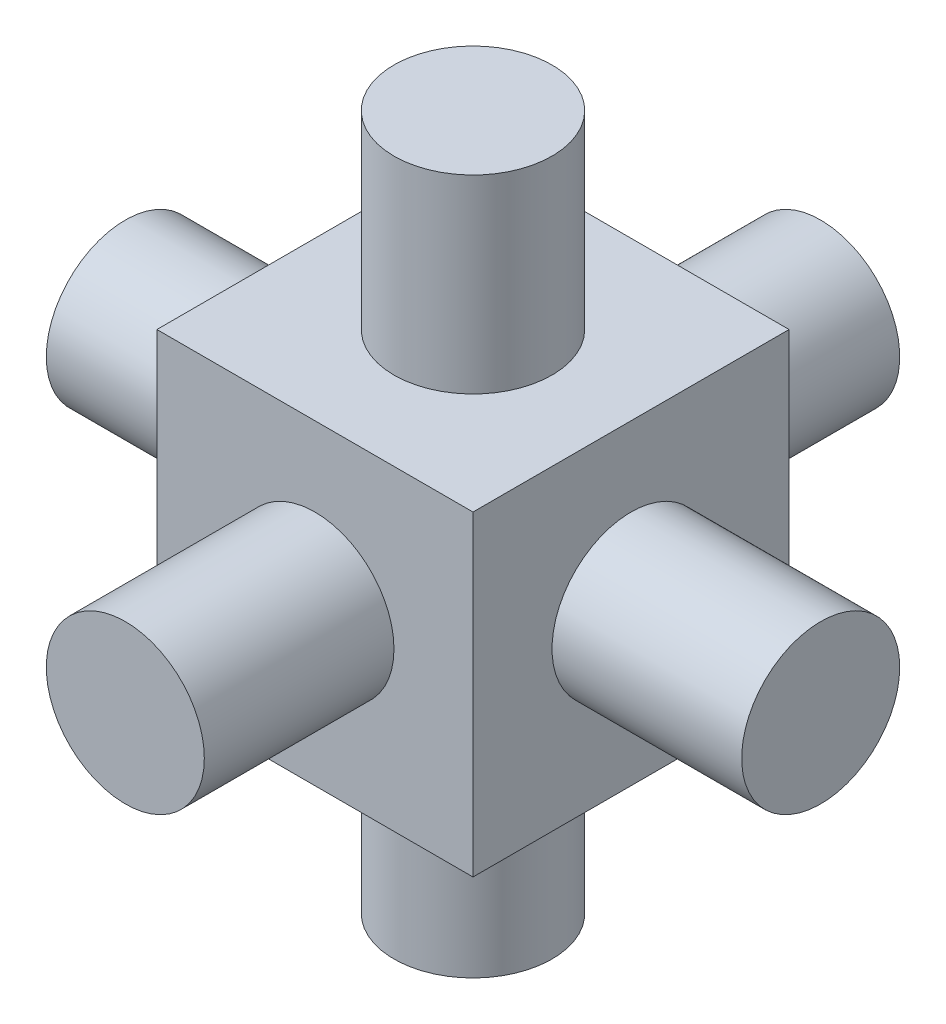
SolidWorks part; units mm, degrees
ref_plane "Plano frontal" through (0, 0, 0) normal (0, 0, 1) x (1, 0, 0)
ref_plane "Plano superior" through (0, 0, 0) normal (0, 1, 0) x (1, 0, 0)
ref_plane "Plano direito" through (0, 0, 0) normal (1, 0, 0) x (0, 0, -1)
sketch "Esboço1" plane through (0, 0, 0) normal (0, 0, 1) x (1, 0, 0)
  line L1 (-10, -10) -> (10, -10)
  line L2 (-10, -10) -> (-10, 10)
  line L3 (-10, 10) -> (10, 10)
  line L4 (10, -10) -> (10, 10)
  line L5 (-10, -10) -> (10, 10) construction
  line L6 (-10, 10) -> (10, -10) construction
  point P0 (0, 0)
  dimension "D1" = 20
  dimension "D2" = 20
extrude "Ressalto-extrusão1" add sketch "Esboço1" along normal blind 20
sketch "Esboço2" plane through (10, 0, 0) normal (1, 0, 0) x (0, 0, -1)
  circle A1 centre (-10, 0) radius 5
extrude "Ressalto-extrusão2" add sketch "Esboço2" along normal blind 12
sketch "Esboço3" plane through (0, 10, 0) normal (0, 1, 0) x (1, 0, 0)
  circle A0 centre (0, -10) radius 5
extrude "Ressalto-extrusão3" add sketch "Esboço3" along normal blind 12
sketch "Esboço4" plane through (-10, 0, 0) normal (-1, 0, 0) x (0, 0, 1)
  circle A0 centre (10, 0) radius 5
extrude "Ressalto-extrusão4" add sketch "Esboço4" along normal blind 12
sketch "Esboço5" plane through (0, -10, 0) normal (0, -1, 0) x (1, 0, 0)
  circle A0 centre (0, 10) radius 5
extrude "Ressalto-extrusão5" add sketch "Esboço5" along normal blind 12
sketch "Esboço6" plane through (0, 0, 0) normal (0, 0, -1) x (-1, 0, 0)
  circle A0 centre (0, 0) radius 5
extrude "Ressalto-extrusão6" add sketch "Esboço6" along normal blind 12
sketch "Esboço7" plane through (0, 0, 20) normal (0, 0, 1) x (1, 0, 0)
  circle A0 centre (0, 0) radius 5
extrude "Ressalto-extrusão7" add sketch "Esboço7" along normal blind 12
